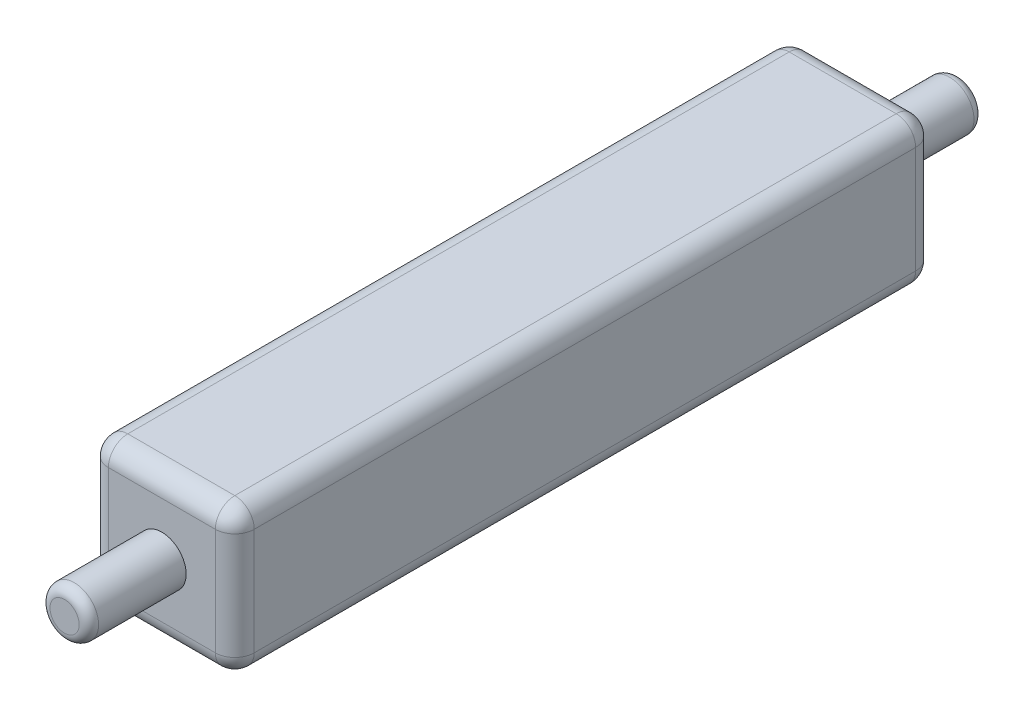
SolidWorks part; units mm, degrees
material "PVC 0.007 Plasticized"
ref_plane "Front Plane" through (0, 0, 0) normal (0, 0, 1) x (1, 0, 0)
ref_plane "Top Plane" through (0, 0, 0) normal (0, 1, 0) x (1, 0, 0)
ref_plane "Right Plane" through (0, 0, 0) normal (1, 0, 0) x (0, 0, -1)
sketch "Sketch1" plane through (0, 0, 0) normal (0, 0, 1) x (1, 0, 0)
  line L1 (0, 0) -> (-15, 0)
  line L2 (0, 0) -> (0, 15)
  line L3 (0, 15) -> (-15, 15)
  line L4 (-15, 0) -> (-15, 15)
  dimension "D1" = 15
  dimension "D2" = 15
extrude "Boss-Extrude1" add sketch "Sketch1" along normal blind 72
sketch "Sketch2" plane through (0, 0, 0) normal (0, 0, -1) x (-1, 0, 0)
  line L0 (15, 15) -> (15, 0) construction
  line L1 (15, 0) -> (0, 0) construction
  circle A0 centre (7.5, 7.5) radius 2.5
  dimension "D1" = 5
  dimension "D3" = 7.5
  dimension "D2" = 7.5
extrude "Boss-Extrude2" add sketch "Sketch2" along normal blind 10
sketch "Sketch3" plane through (0, 0, 72) normal (0, 0, 1) x (1, 0, 0)
  line L0 (0, 15) -> (-15, 15) construction
  line L2 (-15, 15) -> (-15, 0) construction
  circle A0 centre (-7.5, 7.5) radius 2.5
  dimension "D1" = 7.5
  dimension "D2" = 7.5
  dimension "D3" = 5
extrude "Boss-Extrude3" add sketch "Sketch3" along normal blind 10
sketch "Sketch4" plane through (-15, 0, 0) normal (-1, 0, 0) x (0, 0, 1)
  line L0 (0, 7.5) -> (72, 7.5)
  line L1 (0, 15) -> (0, 0) construction
  line L2 (72, 15) -> (72, 0) construction
sketch "Sketch5" plane through (-15, 0, 0) normal (-1, 0, 0) x (0, 0, 1)
  line L0 (20, 7.3064) -> (10, 7.3064) construction
  line L1 (20, 6.3064) -> (10, 6.3064)
  line L2 (20, 8.3064) -> (10, 8.3064)
  line L3 (52, 7.3064) -> (62, 7.3064) construction
  line L4 (52, 8.3064) -> (62, 8.3064)
  line L5 (52, 6.3064) -> (62, 6.3064)
  line L6 (0, 15) -> (0, 0) construction
  line L7 (72, 15) -> (72, 0) construction
  arc A0 (20, 6.3064) -> (20, 8.3064) centre (20, 7.3064) ccw
  arc A1 (10, 8.3064) -> (10, 6.3064) centre (10, 7.3064) ccw
  arc A2 (52, 8.3064) -> (52, 6.3064) centre (52, 7.3064) ccw
  arc A3 (62, 6.3064) -> (62, 8.3064) centre (62, 7.3064) ccw
  point P2 (15, 7.3064)
  point P7 (57, 7.3064)
  dimension "D3" = 1
  dimension "D4" = 1
  dimension "D6" = 10
  dimension "D1" = 10
  dimension "D2" = 10
  dimension "D5" = 10
extrude "Cut-Extrude1" cut sketch "Sketch5" against normal blind 10
fillet "Fillet1" radius 2 1 edges at (-15, 15, 36)
fillet "Fillet2" radius 2 1 edges at (0, 15, 36)
fillet "Fillet3" radius 2 1 edges at (0, 0, 36)
fillet "Fillet4" radius 2 1 edges at (-15, 0, 36)
fillet "Fillet5" radius 2 8 edges at (-15, 7.5, 0) (-14.4142, 14.4142, 0) (-7.5, 15, 0) (-0.5858, 14.4142, 0) (0, 7.5, 0) (-0.5858, 0.5858, 0) (-7.5, 0, 0) (-14.4142, 0.5858, 0)
fillet "Fillet6" radius 2 8 edges at (-15, 7.5, 72) (-14.4142, 14.4142, 72) (-7.5, 15, 72) (-0.5858, 14.4142, 72) (0, 7.5, 72) (-0.5858, 0.5858, 72) (-7.5, 0, 72) (-14.4142, 0.5858, 72)
fillet "Fillet7" radius 1 1 edges at (-5, 7.5, 82)
fillet "Fillet8" radius 1 1 edges at (-10, 7.5, -10)
ref_point "Point1"
ref_plane "Plane1" through (0, 0, 36) normal (0, 0, -1) x (-1, 0, 0)
